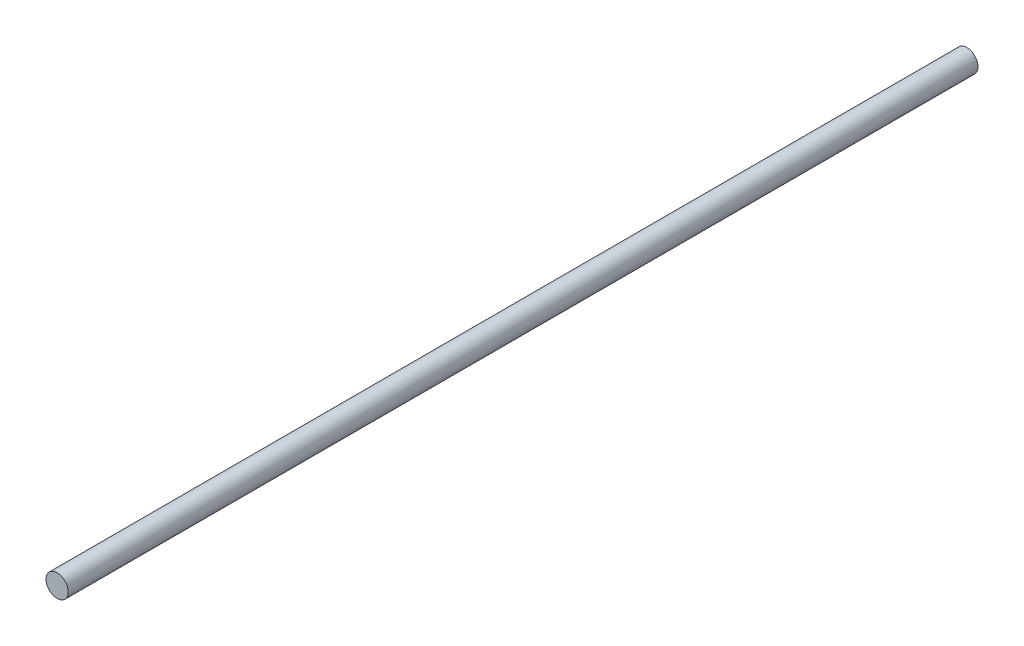
SolidWorks part; units mm, degrees
ref_plane "Front Plane" through (0, 0, 0) normal (0, 0, 1) x (1, 0, 0)
ref_plane "Top Plane" through (0, 0, 0) normal (0, 1, 0) x (1, 0, 0)
ref_plane "Right Plane" through (0, 0, 0) normal (1, 0, 0) x (0, 0, -1)
sketch "Sketch1" plane through (0, 0, 0) normal (0, 0, 1) x (1, 0, 0)
  circle A0 centre (0, 0) radius 3
  dimension "D1" = 6
extrude "Boss-Extrude1" add sketch "Sketch1" along normal blind 245
